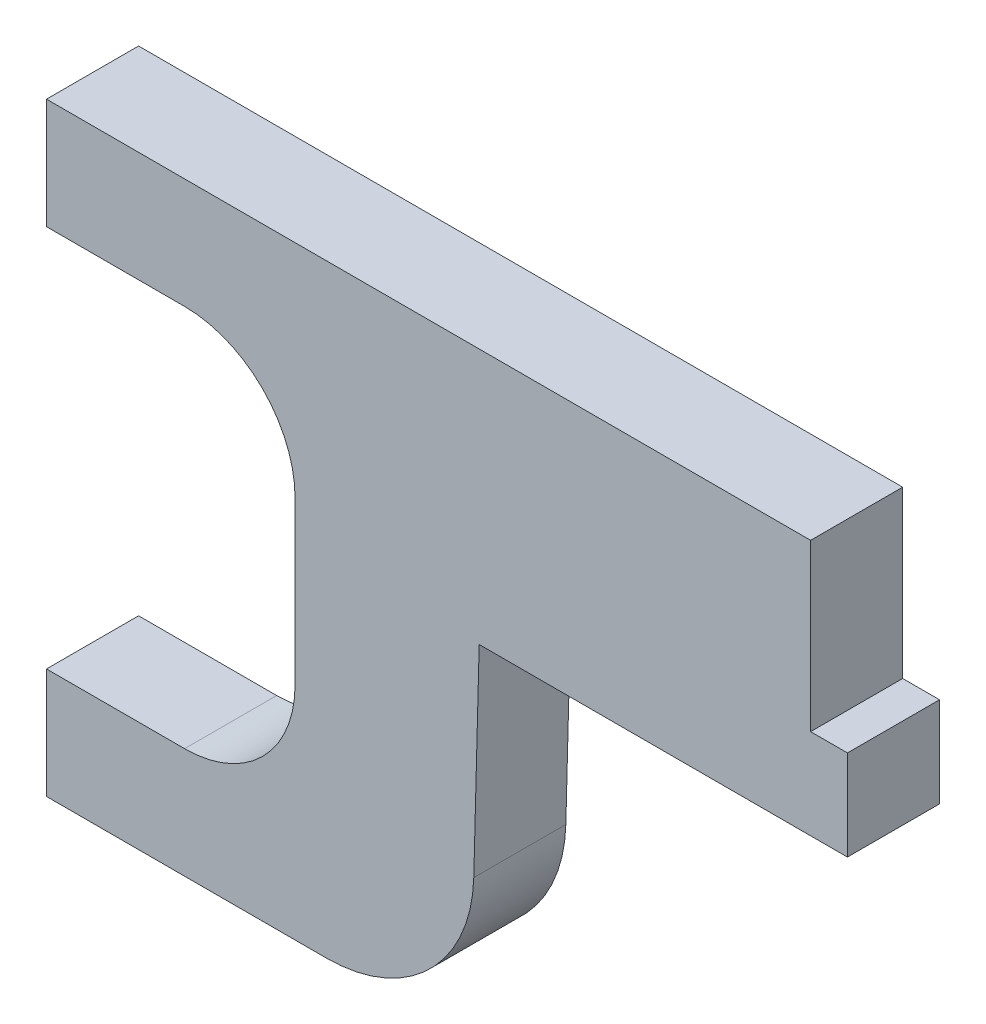
SolidWorks part; units mm, degrees
material "PBT General Purpose"
ref_plane "Front Plane" through (0, 0, 0) normal (0, 0, 1) x (1, 0, 0)
ref_plane "Top Plane" through (0, 0, 0) normal (0, 1, 0) x (1, 0, 0)
ref_plane "Right Plane" through (0, 0, 0) normal (1, 0, 0) x (0, 0, -1)
sketch "frame_outline" plane through (0, 0, 0) normal (0, 0, 1) x (1, 0, 0)
  line L89 (0, 1.64) -> (0, 1.34)
  line L99 (0, 1.34) -> (0.675, 1.34)
  line L100 (0.675, 1.34) -> (0.675, 0.3)
  line L101 (0.675, 0.3) -> (0, 0.3)
  line L102 (0, 0.3) -> (0, 0)
  line L103 (0, 0) -> (1.15, 0)
  line L105 (1.15, 0) -> (1.175, 0.945)
  line L108 (2.075, 1.64) -> (0.7, 1.64)
  line L109 (0.7, 1.64) -> (0, 1.64)
  line L110 (0.675, 0.82) -> (2.391, 0.82) construction
  line L112 (1.175, 0.945) -> (2.175, 0.945)
  line L113 (2.175, 0.945) -> (2.175, 1.19)
  line L115 (2.075, 1.64) -> (2.075, 1.19)
  line L116 (2.075, 1.19) -> (2.175, 1.19)
  dimension "D1" = 0.3
  dimension "D2" = 0.3
  dimension "D9" = 1.64
  dimension "D10" = 0.675
  dimension "D14" = 1.15
  dimension "D15" = 0.7
  dimension "D4" = 1
  dimension "D5" = 0.5
  dimension "D7" = 0.45
  dimension "D3" = 0.125
  dimension "D6" = 0.1
  dimension "D8" = 0.245
  dimension "D11" = 0.695
extrude "Boss-Extrude1" add sketch "frame_outline" along normal mid plane 0.25
fillet "Fillet1" radius 0.3 2 edges at (0.675, 0.3, 0) (0.675, 1.34, 0)
fillet "Fillet2" radius 0.4 1 edges at (1.15, 0, 0)
equation "\"t\"= 0.25'thickness of the sheets"
equation "\"t_cf\" = 0.115'thickness of single carbon fiber layer"
equation "\"t_kapton\" = 0.025'thickness of single Kapton flex layer"
equation "\"t_fr4\" = 0.1'thickness of FR4 with copper layer"
equation "\"joint_flex\"= 0.1'Width of flextures gap"
equation "\"joint_flex_eff\"= 0.02'Width of flecture after castelation"
equation "\"joint_fold\"= 0.2'Width of folding joints for 90deg fold"
equation "\"gap_tolerance\"= 0.002'Width to have interfecence fit between carbon fiber inserts"
equation "\"assemble_angle\"= 90'Angle of assembly parts"
equation "\"D1@Boss-Extrude1\"=\"t\""
equation "\"link_lift\"= 0.5'Actuation linkage amplification for the lift motion"
equation "\"link_swing\"= 0.45'Actuation linkage amplification for the swing motion"
equation "\"D10@frame_outline\"=\"t\"*1.5+0.3+0.1-\"joint_flex\""
equation "\"D3@frame_outline\"=\"t\"/2"
equation "\"D6@frame_outline\"=\"joint_fold\"/2"
equation "\"D7@frame_outline\"=0.40mm+0.05"
